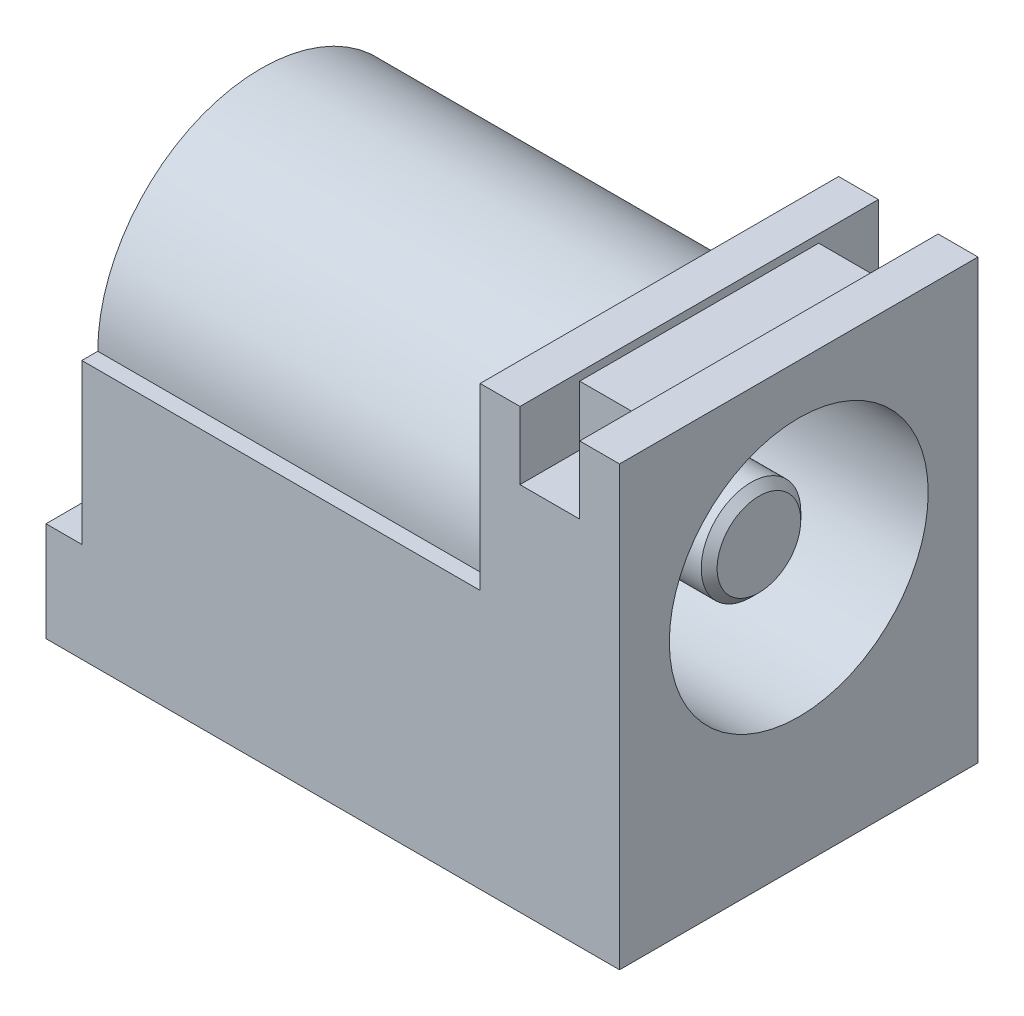
SolidWorks part; units mm, degrees
ref_plane "Front Plane" through (0, 0, 0) normal (0, 0, 1) x (1, 0, 0)
ref_plane "Top Plane" through (0, 0, 0) normal (0, 1, 0) x (1, 0, 0)
ref_plane "Right Plane" through (0, 0, 0) normal (1, 0, 0) x (0, 0, -1)
ref_plane "Plane1" through (-11.95, 0, 0) normal (-1, 0, 0) x (0, -1, 0)
sketch "Sketch1" plane through (-11.95, 0, 0) normal (-1, 0, 0) x (0, -1, 0)
  line L0 (-4.5, 4.5) -> (-4.5, -4.5)
  line L1 (-4.5, -4.5) -> (6.5, -4.5)
  line L2 (6.5, -4.5) -> (6.5, 4.5)
  line L3 (6.5, 4.5) -> (-4.5, 4.5)
extrude "Boss-Extrude1" add sketch "Sketch1" against normal blind 2.5
sketch "Sketch2" plane through (0, 0, -4.5) normal (0, 0, -1) x (-1, 0, 0)
  line L0 (10.2, -9.5) -> (10.2, -7.0043)
  line L1 (10.2, -7.0043) -> (9.45, -6.2)
  line L2 (9.45, -6.2) -> (9.45, 4.5)
  line L3 (9.45, 4.5) -> (11.95, 4.5)
  line L4 (11.95, 4.5) -> (11.95, -6.2)
  line L5 (11.95, -6.2) -> (11.2, -7.0043)
  line L6 (11.2, -7.0043) -> (11.2, -9.5)
  arc A0 (11.2, -9.5) -> (10.2, -9.5) centre (10.7, -9.5) cw
extrude "Boss-Extrude2" add sketch "Sketch2" along normal blind 0.4
sketch "Sketch3" plane through (-9.45, 0, 0) normal (1, 0, 0) x (0, 0, -1)
  line L0 (4.9, 4.5) -> (4.5, 4.5)
  line L1 (4.5, 4.5) -> (4.5, -3.5)
  line L2 (4.9, -3.9899) -> (4.9, 4.5)
  arc A0 (4.5, -3.5) -> (4.9, -3.9899) centre (4.4, -3.9899) cw
extrude "Cut-Extrude1" cut sketch "Sketch3" against normal through all
sketch "Sketch4" plane through (-11.95, 0, 0) normal (-1, 0, 0) x (0, 0, 1)
  line L0 (4.5, 4.5) -> (4.5, -6.5)
  line L1 (4.5, -6.5) -> (-4.5, -6.5)
  line L2 (-4.5, -6.5) -> (-4.5, 4.5)
  line L3 (-4.5, 4.5) -> (4.5, 4.5)
extrude "Boss-Extrude3" add sketch "Sketch4" along normal blind 2.45
sketch "Sketch5" plane through (-9.45, 0, 0) normal (1, 0, 0) x (0, 0, -1)
  line L0 (-4.5, -6.5) -> (-4.5, 4.5)
  line L1 (-4.5, 4.5) -> (4.5, 4.5)
  line L2 (4.5, 4.5) -> (4.5, -6.5)
  line L3 (4.5, -6.5) -> (-4.5, -6.5)
extrude "Boss-Extrude4" add sketch "Sketch5" along normal blind 9.45
sketch "Sketch6" plane through (0, 0, 4.5) normal (0, 0, 1) x (1, 0, 0)
  line L0 (-14.4, 4.5) -> (-14.4, -4)
  line L1 (-14.4, -4) -> (-13.5, -4)
  line L2 (-13.5, -4) -> (-13.5, 4.5)
  line L3 (-13.5, 4.5) -> (-14.4, 4.5)
extrude "Cut-Extrude2" cut sketch "Sketch6" against normal through all
sketch "Sketch7" plane through (0, -4, 0) normal (0, 1, 0) x (-1, 0, 0)
  line L0 (13.88, 1.5) -> (13.88, -4.5)
  line L1 (13.88, -4.5) -> (14.4, -4.5)
  line L2 (14.4, -4.5) -> (14.4, 1.5)
  line L3 (14.4, 1.5) -> (13.88, 1.5)
extrude "Cut-Extrude3" cut sketch "Sketch7" against normal through all
ref_plane "Plane2" through (-13.88, 0, 0) normal (-1, 0, 0) x (0, -1, 0)
sketch "Sketch8" plane through (-13.88, 0, 0) normal (-1, 0, 0) x (0, -1, 0)
  line L0 (4, -1.5) -> (4, 1.5)
  line L1 (4, 1.5) -> (-1.62, 1.5)
  line L2 (-1.62, 1.5) -> (-1.62, -1.5)
  line L3 (-1.62, -1.5) -> (4, -1.5)
extrude "Boss-Extrude5" add sketch "Sketch8" against normal blind 0.36
sketch "Sketch9" plane through (-13.88, 0, 0) normal (-1, 0, 0) x (0, 0, 1)
  line L0 (-1.5, -6.5) -> (-4.5, -6.5)
  line L1 (-4.5, -6.5) -> (-4.5, -4)
  line L2 (-4.5, -4) -> (-1.5, -4)
  line L3 (-1.5, -4) -> (-1.5, -6.5)
extrude "Boss-Extrude6" add sketch "Sketch9" along normal blind 0.52
ref_plane "Plane3" through (-13.52, 0, 0) normal (1, 0, 0) x (0, 0, -1)
sketch "Sketch11" plane through (-13.52, 0, 0) normal (1, 0, 0) x (0, 0, -1)
  line L0 (0.5, -6.4) -> (0.5, -6.5)
  line L1 (0.5, -6.5) -> (1.5, -6.5)
  line L2 (1.5, -6.5) -> (1.5, -6.4)
  line L3 (1.5, -6.4) -> (0.5, -6.4)
extrude "Cut-Extrude4" cut sketch "Sketch11" against normal up to surface up to plane "Plane2"
sketch "Sketch12" plane through (-13.88, 0, 0) normal (-1, 0, 0) x (0, -1, 0)
  line L0 (9.5, 0.5) -> (6.5, 0.5)
  line L1 (6.5, 0.5) -> (6.5, -0.5)
  line L2 (6.5, -0.5) -> (9.5, -0.5)
  arc A0 (9.5, -0.5) -> (9.5, 0.5) centre (9.5, 0) ccw
extrude "Boss-Extrude7" add sketch "Sketch12" against normal blind 0.36
ref_plane "Plane4" through (0, -6.5, 0) normal (0, -1, 0) x (1, 0, 0)
ref_plane "Plane5" through (0, -5.3276, 0) normal (0, 1, 0) x (1, 0, 0)
sketch "Sketch14" plane through (0, -5.3276, 0) normal (0, 1, 0) x (1, 0, 0)
  line L0 (-13.52, -1.5) -> (-13.52, -0.5)
  line L1 (-13.52, -0.5) -> (-13.88, -0.5)
  line L2 (-13.88, -0.5) -> (-13.88, -1.5)
  line L3 (-13.88, -1.5) -> (-13.52, -1.5)
extrude "Cut-Extrude5" cut sketch "Sketch14" against normal up to surface up to plane "Plane4"
sketch "Sketch15" plane through (0, 0, -4.5) normal (0, 0, -1) x (-1, 0, 0)
  line L0 (3.5, 4.5) -> (3.5, 0)
  line L1 (3.5, 0) -> (13.5, 0)
  line L2 (13.5, 0) -> (13.5, 4.5)
  line L3 (13.5, 4.5) -> (3.5, 4.5)
extrude "Cut-Extrude6" cut sketch "Sketch15" against normal through all
sketch "Sketch16" plane through (-3.5, 0, 0) normal (-1, 0, 0) x (0, 0, 1)
  line L0 (4.1, 0) -> (-4.1, 0)
  arc A0 (-4.1, 0) -> (4.1, 0) centre (0, 0) cw
extrude "Boss-Extrude8" add sketch "Sketch16" along normal blind 10
sketch "Sketch17" plane through (0, 0, -4.5) normal (0, 0, -1) x (-1, 0, 0)
  line L0 (2.5, 4.5) -> (1, 4.5)
  line L1 (1, 4.5) -> (1, 2.8)
  line L2 (1, 2.8) -> (2.5, 2.8)
  line L3 (2.5, 2.8) -> (2.5, 4.5)
extrude "Cut-Extrude7" cut sketch "Sketch17" against normal through all
sketch "Sketch18" plane through (-2.5, 0, 0) normal (1, 0, 0) x (0, 0, -1)
  line L0 (3, 4.3) -> (3, 2.8)
  line L1 (3, 2.8) -> (-3, 2.8)
  line L2 (-3, 2.8) -> (-3, 4.3)
  line L3 (-3, 4.3) -> (3, 4.3)
extrude "Boss-Extrude9" add sketch "Sketch18" along normal blind 1.5
ref_plane "Plane6" through (-7.825, 0, 0) normal (-1, 0, 0) x (0, -1, 0)
sketch "Sketch19" plane through (-7.825, 0, 0) normal (-1, 0, 0) x (0, -1, 0)
  line L0 (9.5, 0.5) -> (6.5, 0.5)
  line L1 (6.5, 0.5) -> (6.5, -0.5)
  line L2 (6.5, -0.5) -> (9.5, -0.5)
  arc A0 (9.5, -0.5) -> (9.5, 0.5) centre (9.5, 0) ccw
extrude "Boss-Extrude10" add sketch "Sketch19" against normal blind 0.25
hole_wizard "Ø6.5 (6.5) Diameter Hole1" positions "Sketch21" profile "Sketch20" hole size "Ø6.5" standard "ANSI Metric"
sketch "Sketch21" plane through (0, 0, 0) normal (1, 0, 0) x (0, 0, -1)
  point P0 (0, 0)
sketch "Sketch20" plane through (0, 0, 0) normal (0, 1, 0) x (0, 0, -1)
  line L0 (0, 0) -> (0, 7)
  line L1 (0, 7) -> (3.25, 7)
  line L2 (3.25, 7) -> (3.25, 0)
  line L5 (3.25, 0) -> (0, 0)
  line L10 (0, 7) -> (-3.25, 7) construction
  line L11 (0, -6.35) -> (0, 107.95) construction
  dimension "Hole Dia." = 6.5
  dimension "Hole Depth" = 7
  dimension "Drill Angle" = 180
draft "Draft1" type of draft neutral plane draft angle 47 faces to draft 1 face at (-13.7, -5.3276, 1) neutral plane through (-14.4, -10, 1.5) neutral plane normal (0, 0, -1) reverse direction yes parameters "D1"=47
draft "Draft2" type of draft neutral plane draft angle 47 faces to draft 1 face at (-13.7, -6.4, -1) neutral plane through (-14.885, -6.4, -0.5) neutral plane normal (0, 0, -1) parameters "D1"=47
sketch "Sketch22" plane through (0, 0, 0) normal (0, 0, 1) x (1, 0, 0)
  line L0 (-7, 1.25) -> (-7, 0)
  line L1 (-7, 0) -> (-1, 0)
  line L2 (-1, 0) -> (-1, 1.25)
  line L3 (-1, 1.25) -> (-7, 1.25)
  line L4 (-7, 0) -> (-1, 0) construction
revolve "Revolve1" add sketch "Sketch22" angle 360 about L4
chamfer "Chamfer1" distance 0.2 angle 45 1 edges at (-1, 0, -1.25)
